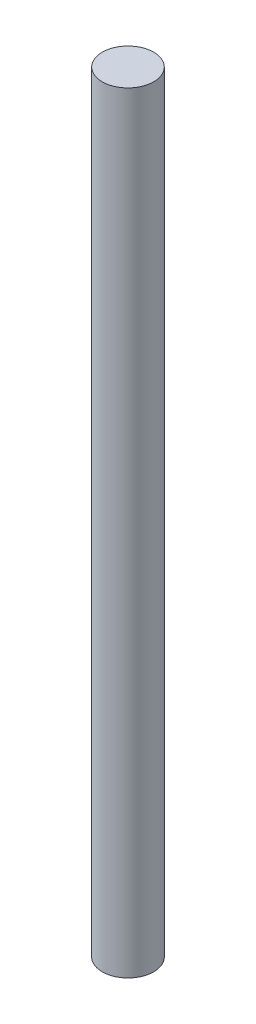
SolidWorks part; units mm, degrees
material "AISI 1020"
ref_plane "Plano frontal" through (0, 0, 0) normal (0, 0, 1) x (1, 0, 0)
ref_plane "Plano superior" through (0, 0, 0) normal (0, 1, 0) x (1, 0, 0)
ref_plane "Plano direito" through (0, 0, 0) normal (1, 0, 0) x (0, 0, -1)
sketch "Esboço1" plane through (0, 0, 0) normal (0, 1, 0) x (1, 0, 0)
  circle A0 centre (0, 0) radius 5
  dimension "D1" = 10
extrude "Ressalto-extrusão1" add sketch "Esboço1" along normal blind 150
